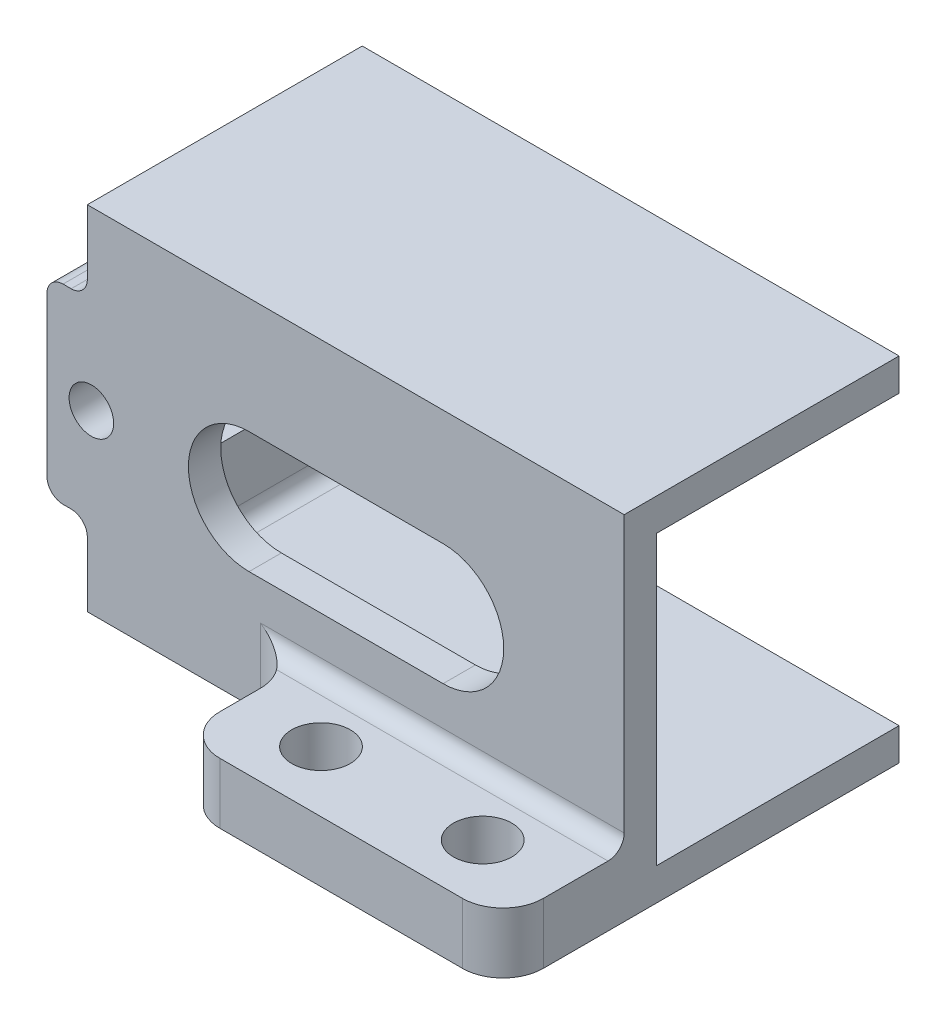
SolidWorks part; units mm, degrees
ref_plane "Front Plane" through (0, 0, 0) normal (0, 0, 1) x (1, 0, 0)
ref_plane "Top Plane" through (0, 0, 0) normal (0, 1, 0) x (1, 0, 0)
ref_plane "Right Plane" through (0, 0, 0) normal (1, 0, 0) x (0, 0, -1)
sketch "Sketch1" plane through (0, 0, 0) normal (0, 0, 1) x (1, 0, 0)
  line L0 (-2.54, 25.146) -> (39.624, 25.146)
  line L1 (0, 0) -> (37.084, 0)
  line L2 (0, 0) -> (0, 22.606)
  line L3 (0, 22.606) -> (37.084, 22.606)
  line L5 (39.624, -2.54) -> (39.624, 0)
  line L6 (-2.54, -2.54) -> (39.624, -2.54)
  line L7 (-2.54, -2.54) -> (-2.54, 25.146)
  line L8 (37.084, 0) -> (37.084, 22.606) construction
  line L9 (37.084, 22.606) -> (39.624, 22.606)
  line L10 (37.084, 0) -> (39.624, 0)
  line L11 (39.624, 22.606) -> (39.624, 25.146)
  line L12 (39.624, -2.54) -> (39.624, 25.146) construction
  dimension "D1" = 22.606
  dimension "D2" = 37.084
  dimension "D3" = 2.54
extrude "Boss-Extrude1" add sketch "Sketch1" along normal blind 19.05
sketch "Sketch2" plane through (0, 0, 19.05) normal (0, 0, 1) x (1, 0, 0)
  line L1 (-2.54, 25.146) -> (39.624, 25.146)
  line L2 (-2.54, 25.146) -> (-2.54, -2.54)
  line L3 (-2.54, -2.54) -> (39.624, -2.54)
  line L4 (39.624, 25.146) -> (39.624, -2.54)
extrude "Boss-Extrude2" add sketch "Sketch2" along normal blind 2.54
sketch "Sketch3" plane through (-2.54, 0, 0) normal (-1, 0, 0) x (0, 0, 1)
  line L1 (21.59, 18.796) -> (14.5288, 18.796)
  line L2 (21.59, 18.796) -> (21.59, 3.81)
  line L3 (21.59, 3.81) -> (14.5288, 3.81)
  line L4 (14.5288, 18.796) -> (14.5288, 3.81)
  line L5 (21.59, 25.146) -> (0, 25.146) construction
  line L6 (21.59, 25.146) -> (21.59, -2.54) construction
  line L7 (21.59, -2.54) -> (0, -2.54) construction
  dimension "D1" = 6.35
  dimension "D2" = 7.0612
  dimension "D3" = 6.35
extrude "Boss-Extrude3" add sketch "Sketch3" along normal blind 3.175
sketch "Sketch4" plane through (0, 0, 14.5288) normal (0, 0, -1) x (-1, 0, 0)
  line L0 (0, 0) -> (0, 22.606) construction
  line L1 (5.715, 18.796) -> (5.715, 3.81) construction
  circle A0 centre (2.2225, 11.303) radius 1.75
  point P6 (5.715, 11.303)
  dimension "D1" = 3.5
  dimension "D2" = 2.2225
extrude "Cut-Extrude1" cut sketch "Sketch4" against normal through all both and the other way through all
fillet "Fillet2" radius 1.27 4 edges at (-5.715, 3.81, 18.0594) (-2.54, 3.81, 18.0594) (-2.54, 18.796, 18.0594) (-5.715, 18.796, 18.0594)
sketch "Sketch5" plane through (0, 0, 21.59) normal (0, 0, 1) x (1, 0, 0)
  line L0 (39.624, -2.54) -> (39.624, 25.146) construction
  line L1 (-2.54, 20.066) -> (-2.54, 2.54) construction
  line L2 (10.16, 16.0655) -> (25.4, 16.0655)
  line L3 (10.16, 6.5405) -> (25.4, 6.5405)
  circle A0 centre (10.16, 11.303) radius 4.7625
  circle A1 centre (25.4, 11.303) radius 4.7625
  point P5 (39.624, 11.303)
  dimension "D1" = 9.525
  dimension "D2" = 12.7
  dimension "D3" = 15.24
extrude "Cut-Extrude2" cut sketch "Sketch5" against normal through all both contours A0 | A1 L2 A0 L3 | A1
sketch "Sketch6" plane through (0, 0, 21.59) normal (0, 0, 1) x (1, 0, 0)
  line L0 (39.624, 25.146) -> (-2.54, 25.146) construction
  line L1 (14.224, 25.146) -> (39.624, 25.146)
  line L2 (14.224, 25.146) -> (14.224, 20.3835)
  line L3 (14.224, 20.3835) -> (39.624, 20.3835)
  line L4 (39.624, 25.146) -> (39.624, 20.3835)
  line L7 (39.624, -2.54) -> (39.624, 25.146) construction
  point P6 (26.924, 20.3835)
  dimension "D1" = 4.7625
  dimension "D2" = 25.4
  dimension "D3" = 12.7
extrude "Boss-Extrude4" add sketch "Sketch6" along normal blind 9.525
fillet "Fillet3" radius 3.175 3 edges at (39.624, 22.7647, 31.115) (14.224, 22.7647, 31.115) (14.224, 22.7647, 21.59)
fillet "Fillet4" radius 1.27 1 edges at (25.3365, 20.3835, 21.59)
fillet "Fillet6" radius 1.27 2 edges at (0, 0, 9.525) (0, 22.606, 9.525)
sketch "Sketch8" plane through (0, 25.146, 0) normal (0, 1, 0) x (1, 0, 0)
  line L1 (14.224, -24.765) -> (14.224, -21.59) construction
  line L2 (26.924, -21.59) -> (26.924, -31.115) construction
  line L3 (36.449, -31.115) -> (17.399, -31.115) construction
  line L4 (14.224, -21.59) -> (26.924, -21.59) construction
  line L5 (26.924, -21.59) -> (39.624, -21.59) construction
  circle A0 centre (20.574, -26.3525) radius 2.3
  circle A1 centre (33.274, -26.3525) radius 2.3
  point P14 (26.924, -26.3525)
  point P15 (33.274, -21.59)
  point P16 (20.574, -21.59)
  dimension "D1" = 4.6
  dimension "D2" = 4.6
extrude "Cut-Extrude3" cut sketch "Sketch8" against normal through all both
sketch "Sketch9" plane through (0, 0, 0) normal (0, 0, -1) x (-1, 0, 0)
  line L0 (0, 1.27) -> (0, 21.336) construction
  line L1 (0, 16.383) -> (2.54, 16.383)
  line L2 (0, 16.383) -> (0, 6.223)
  line L3 (0, 6.223) -> (2.54, 6.223)
  line L4 (2.54, 16.383) -> (2.54, 6.223)
  line L5 (2.54, 20.066) -> (2.54, 13.024) construction
  point P8 (0, 11.303)
  dimension "D1" = 10.16
extrude "Cut-Extrude4" cut sketch "Sketch9" against normal up to surface (14.5288 mm away) up to face at (-3.9533, 11.303, 14.5288)
ref_plane "Plane2" through (0, 11.303, 0) normal (0, 1, 0) x (1, 0, 0)
mirror "Mirror2" about plane through (0, 11.303, 0) normal (0, 1, 0) of "Fillet4", "Cut-Extrude3", "Boss-Extrude4", "Fillet3"
sketch "Sketch11" plane through (0, 25.146, 0) normal (0, 1, 0) x (1, 0, 0)
  line L1 (-2.54, -21.59) -> (41.2954, -21.59)
  line L2 (-2.54, -21.59) -> (-2.54, -32.4886)
  line L3 (-2.54, -32.4886) -> (41.2954, -32.4886)
  line L4 (41.2954, -21.59) -> (41.2954, -32.4886)
extrude "Cut-Extrude5" cut sketch "Sketch11" against normal blind 6.858
